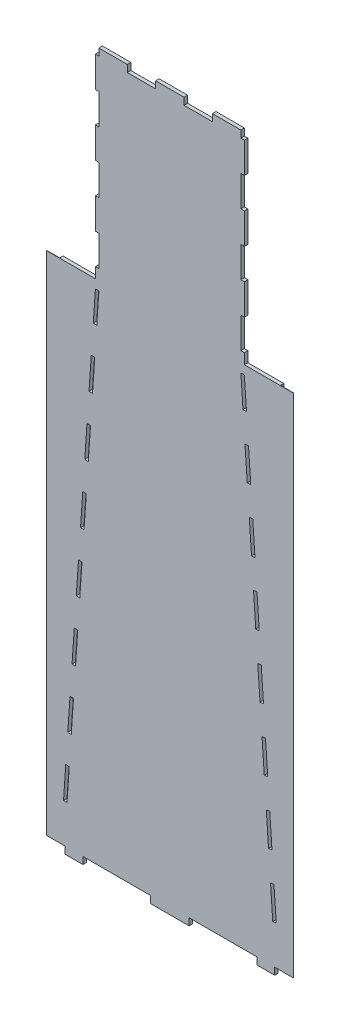
SolidWorks part; units mm, degrees
material "A-Glass Fiber"
ref_plane "Front Plane" through (0, 0, 0) normal (0, 0, 1) x (1, 0, 0)
ref_plane "Top Plane" through (0, 0, 0) normal (0, 1, 0) x (1, 0, 0)
ref_plane "Right Plane" through (0, 0, 0) normal (1, 0, 0) x (0, 0, -1)
sketch "Sketch1" plane through (0, 0, 0) normal (0, 0, 1) x (1, 0, 0)
  line L0 (-215.8818, 2072.64) -> (-215.8818, 1463.04) construction
  line L1 (308.2661, 132.944) -> (301.7555, 226.6808) construction
  line L2 (-303.52, 0) -> (252, 0) construction
  line L3 (-215.8818, 2072.64) -> (215.8818, 2072.64) construction
  line L4 (301.7555, 226.6808) -> (291.6378, 225.9781) construction
  line L5 (-205.7153, 2072.64) -> (-123.444, 2072.64)
  line L6 (-123.444, 2052.32) -> (-123.444, 2072.64)
  line L7 (-123.444, 2052.32) -> (-123.444, 2072.64)
  line L8 (-41.1356, 2072.64) -> (-41.1356, 2052.32)
  line L9 (-41.1356, 2072.64) -> (41.1356, 2072.64)
  line L10 (0, 2072.64) -> (0, 0) construction
  line L11 (291.6378, 225.9781) -> (298.1484, 132.2412) construction
  line L12 (-252, 20.32) -> (252, 20.32)
  line L13 (298.1484, 132.2412) -> (308.2661, 132.944) construction
  line L14 (289.4357, 404.0535) -> (279.318, 403.3508) construction
  line L15 (279.318, 403.3508) -> (285.8305, 309.5874) construction
  line L16 (285.8305, 309.5874) -> (295.9482, 310.2901) construction
  line L17 (-205.7153, 2072.64) -> (-123.444, 2072.64) construction
  line L18 (-205.7153, 2072.64) -> (-205.7153, 1963.42)
  line L19 (-205.7153, 1963.42) -> (-215.8818, 1963.42)
  line L20 (-215.8818, 2052.32) -> (-215.8818, 1963.42)
  line L21 (-205.7153, 1963.42) -> (-215.8818, 1963.42)
  line L23 (-205.7153, 1874.52) -> (-215.8818, 1874.52)
  line L26 (295.9482, 310.2901) -> (289.4357, 404.0535) construction
  line L28 (205.7153, 1696.72) -> (215.8753, 1696.72)
  line L29 (215.8753, 1696.72) -> (215.8753, 1607.82)
  line L30 (205.7153, 1696.72) -> (215.8753, 1696.72)
  line L31 (205.7153, 1607.82) -> (215.8753, 1607.82)
  line L32 (283.6303, 487.6362) -> (277.1159, 581.4262) construction
  line L33 (205.7153, 1607.82) -> (215.8753, 1607.82)
  line L34 (-205.7153, 1518.92) -> (215.8818, 1518.92)
  line L35 (205.7153, 1785.62) -> (215.8818, 1785.62)
  line L36 (-205.7153, 1518.92) -> (215.8818, 1518.92)
  line L37 (-215.8818, 1463.04) -> (-205.7153, 1463.04)
  line L38 (277.1159, 581.4262) -> (266.9983, 580.7234) construction
  line L39 (-215.8818, 1463.04) -> (-205.7153, 1463.04) construction
  line L40 (-205.7153, 1463.04) -> (-205.7153, 2072.64)
  line L41 (266.9983, 580.7234) -> (273.5126, 486.9335) construction
  line L42 (273.5126, 486.9335) -> (283.6303, 487.6362) construction
  line L43 (264.7962, 758.7989) -> (254.6785, 758.0961) construction
  line L44 (215.8818, 1463.04) -> (205.7153, 1463.04) construction
  line L45 (254.6785, 758.0961) -> (261.1947, 664.2796) construction
  line L46 (261.1947, 664.2796) -> (271.3124, 664.9824) construction
  line L47 (271.3124, 664.9824) -> (264.7962, 758.7989) construction
  line L48 (252.4764, 936.1715) -> (242.3588, 935.4688) construction
  line L50 (242.3588, 935.4688) -> (248.8768, 841.6258) construction
  line L52 (248.8768, 841.6258) -> (258.9945, 842.3285) construction
  line L53 (258.9945, 842.3285) -> (252.4764, 936.1715) construction
  line L54 (240.1567, 1113.5442) -> (230.039, 1112.8414) construction
  line L55 (230.039, 1112.8414) -> (236.5589, 1018.9719) construction
  line L56 (236.5589, 1018.9719) -> (246.6766, 1019.6747) construction
  line L57 (246.6766, 1019.6747) -> (240.1567, 1113.5442) construction
  line L58 (227.8369, 1290.9169) -> (217.7192, 1290.2141) construction
  line L59 (217.7192, 1290.2141) -> (224.241, 1196.3181) construction
  line L60 (224.241, 1196.3181) -> (234.3587, 1197.0208) construction
  line L61 (234.3587, 1197.0208) -> (227.8369, 1290.9169) construction
  line L62 (205.7153, 1463.04) -> (211.9231, 1373.6642) construction
  line L63 (211.9231, 1373.6642) -> (222.0407, 1374.3669) construction
  line L64 (222.0407, 1374.3669) -> (215.8818, 1463.04) construction
  line L65 (215.8818, 1463.04) -> (205.7153, 1463.04) construction
  line L66 (-211.9231, 1373.6642) -> (-205.7153, 1463.04) construction
  line L67 (252, 0) -> (303.52, 0) construction
  line L68 (-205.7153, 1463.04) -> (-215.8818, 1463.04) construction
  line L69 (-215.8818, 1463.04) -> (-222.0407, 1374.3669) construction
  line L70 (-252, 20.32) -> (-252, 0)
  line L71 (-222.0407, 1374.3669) -> (-211.9231, 1373.6642) construction
  line L72 (-217.7192, 1290.2141) -> (-227.8369, 1290.9169) construction
  line L73 (-227.8369, 1290.9169) -> (-234.3587, 1197.0208) construction
  line L74 (-234.3587, 1197.0208) -> (-224.241, 1196.3181) construction
  line L75 (-224.241, 1196.3181) -> (-217.7192, 1290.2141) construction
  line L76 (-230.039, 1112.8414) -> (-240.1567, 1113.5442) construction
  line L77 (-240.1567, 1113.5442) -> (-246.6766, 1019.6747) construction
  line L79 (-246.6766, 1019.6747) -> (-236.5589, 1018.9719) construction
  line L80 (-236.5589, 1018.9719) -> (-230.039, 1112.8414) construction
  line L81 (-242.3588, 935.4688) -> (-252.4764, 936.1715) construction
  line L82 (205.7153, 2072.64) -> (123.444, 2072.64) construction
  line L86 (-205.7153, 2052.32) -> (-215.8818, 2052.32)
  line L89 (-252.4764, 936.1715) -> (-258.9945, 842.3285) construction
  line L90 (215.8818, 2072.64) -> (215.8818, 1463.04) construction
  line L91 (-215.8818, 2052.32) -> (-205.7153, 2052.32)
  line L92 (215.8818, 2052.32) -> (205.7153, 2052.32)
  line L94 (205.7153, 2052.32) -> (-215.8818, 2052.32)
  line L98 (-258.9945, 842.3285) -> (-248.8768, 841.6258) construction
  line L99 (-248.8768, 841.6258) -> (-242.3588, 935.4688) construction
  line L101 (-254.6785, 758.0961) -> (-264.7962, 758.7989) construction
  line L102 (-264.7962, 758.7989) -> (-271.3124, 664.9824) construction
  line L104 (-271.3124, 664.9824) -> (-261.1947, 664.2796) construction
  line L105 (-261.1947, 664.2796) -> (-254.6785, 758.0961) construction
  line L106 (-277.1159, 581.4262) -> (-283.6303, 487.6362) construction
  line L107 (-283.6303, 487.6362) -> (-273.5126, 486.9335) construction
  line L108 (252, 20.32) -> (252, 0)
  line L109 (-273.5126, 486.9335) -> (-266.9983, 580.7234) construction
  line L111 (-266.9983, 580.7234) -> (-277.1159, 581.4262) construction
  line L112 (-279.318, 403.3508) -> (-289.4357, 404.0535) construction
  line L113 (-289.4357, 404.0535) -> (-295.9482, 310.2901) construction
  line L114 (-295.9482, 310.2901) -> (-285.8305, 309.5874) construction
  line L116 (-285.8305, 309.5874) -> (-279.318, 403.3508) construction
  line L117 (-301.7555, 226.6808) -> (-308.2661, 132.944) construction
  line L120 (-308.2661, 132.944) -> (-298.1484, 132.2412) construction
  line L121 (-298.1484, 132.2412) -> (-291.6378, 225.9781) construction
  line L124 (-291.6378, 225.9781) -> (-301.7555, 226.6808) construction
  line L125 (308.2661, 132.944) -> (301.7555, 226.6808)
  line L127 (301.7555, 226.6808) -> (291.6378, 225.9781)
  line L128 (205.7153, 1463.04) -> (205.7153, 2072.64)
  line L129 (215.8818, 1463.04) -> (205.7153, 1463.04)
  line L130 (205.7153, 1518.92) -> (-215.8818, 1518.92)
  line L131 (-205.7153, 1518.92) -> (-215.8818, 1518.92)
  line L132 (205.7153, 1518.92) -> (-215.8818, 1518.92)
  line L133 (-205.7153, 1607.82) -> (-215.8753, 1607.82)
  line L134 (291.6378, 225.9781) -> (298.1484, 132.2412)
  line L135 (-205.7153, 1607.82) -> (-215.8753, 1607.82)
  line L136 (-205.7153, 1696.72) -> (-215.8753, 1696.72)
  line L137 (-215.8753, 1696.72) -> (-215.8753, 1607.82)
  line L138 (-205.7153, 1696.72) -> (-215.8753, 1696.72)
  line L143 (-215.8818, 1518.92) -> (-215.8818, 1463.04)
  line L145 (205.7153, 1963.42) -> (215.8818, 1963.42)
  line L146 (215.8818, 2052.32) -> (215.8818, 1963.42)
  line L147 (205.7153, 1963.42) -> (215.8818, 1963.42)
  line L148 (205.7153, 2072.64) -> (205.7153, 1963.42)
  line L149 (41.1356, 2072.64) -> (41.1356, 2052.32)
  line L150 (123.444, 2052.32) -> (123.444, 2072.64)
  line L151 (123.444, 2052.32) -> (123.444, 2072.64)
  line L152 (205.7153, 2072.64) -> (123.444, 2072.64)
  line L153 (298.1484, 132.2412) -> (308.2661, 132.944)
  line L154 (205.7153, 1518.92) -> (215.8818, 1518.92)
  line L155 (215.8818, 1518.92) -> (215.8818, 1463.04)
  line L156 (-205.7153, 1785.62) -> (-215.8818, 1785.62)
  line L165 (-215.8818, 1874.52) -> (-215.8818, 1785.62)
  line L166 (215.8818, 1874.52) -> (215.8818, 1785.62)
  line L167 (205.7153, 1874.52) -> (215.8818, 1874.52)
  line L168 (215.8818, 1488.44) -> (358.1218, 1488.44)
  line L169 (-55.8292, 20.32) -> (55.8292, 20.32)
  line L170 (-55.8292, 20.32) -> (-55.8292, 0)
  line L171 (-55.8292, 0) -> (55.8292, 0)
  line L172 (55.8292, 20.32) -> (55.8292, 0)
  line L173 (358.1218, 1488.44) -> (358.1218, 20.32)
  line L175 (-215.8818, 1488.44) -> (-358.1218, 1488.44)
  line L176 (-358.1218, 1488.44) -> (-358.1218, 20.32)
  line L178 (289.4357, 404.0535) -> (279.318, 403.3508)
  line L179 (279.318, 403.3508) -> (285.8305, 309.5874)
  line L180 (-371.5407, 0) -> (-280.9748, 0) construction
  line L181 (-358.1218, 20.32) -> (-303.52, 20.32)
  line L184 (-303.52, 20.32) -> (-303.52, 0)
  line L185 (280.9748, 0) -> (371.5407, 0) construction
  line L186 (-303.52, 0) -> (-252, 0)
  line L187 (-303.52, 0) -> (-303.52, 20.32)
  line L189 (-252, 0) -> (-252, 20.32)
  line L190 (358.1218, 20.32) -> (303.52, 20.32)
  line L193 (303.52, 20.32) -> (303.52, 0)
  line L194 (285.8305, 309.5874) -> (295.9482, 310.2901)
  line L195 (303.52, 0) -> (252, 0)
  line L196 (303.52, 0) -> (303.52, 20.32)
  line L198 (252, 0) -> (252, 20.32)
  line L199 (295.9482, 310.2901) -> (289.4357, 404.0535)
  line L200 (283.6303, 487.6362) -> (277.1159, 581.4262)
  line L201 (277.1159, 581.4262) -> (266.9983, 580.7234)
  line L202 (266.9983, 580.7234) -> (273.5126, 486.9335)
  line L203 (273.5126, 486.9335) -> (283.6303, 487.6362)
  line L204 (264.7962, 758.7989) -> (254.6785, 758.0961)
  line L205 (254.6785, 758.0961) -> (261.1947, 664.2796)
  line L206 (261.1947, 664.2796) -> (271.3124, 664.9824)
  line L207 (271.3124, 664.9824) -> (264.7962, 758.7989)
  line L208 (252.4764, 936.1715) -> (242.3588, 935.4688)
  line L209 (242.3588, 935.4688) -> (248.8768, 841.6258)
  line L210 (248.8768, 841.6258) -> (258.9945, 842.3285)
  line L211 (258.9945, 842.3285) -> (252.4764, 936.1715)
  line L212 (240.1567, 1113.5442) -> (230.039, 1112.8414)
  line L213 (230.039, 1112.8414) -> (236.5589, 1018.9719)
  line L214 (236.5589, 1018.9719) -> (246.6766, 1019.6747)
  line L215 (246.6766, 1019.6747) -> (240.1567, 1113.5442)
  line L216 (227.8369, 1290.9169) -> (217.7192, 1290.2141)
  line L217 (217.7192, 1290.2141) -> (224.241, 1196.3181)
  line L218 (224.241, 1196.3181) -> (234.3587, 1197.0208)
  line L219 (234.3587, 1197.0208) -> (227.8369, 1290.9169)
  line L220 (205.7153, 1463.04) -> (211.9231, 1373.6642)
  line L221 (211.9231, 1373.6642) -> (222.0407, 1374.3669)
  line L222 (222.0407, 1374.3669) -> (215.8818, 1463.04)
  line L223 (215.8818, 1463.04) -> (205.7153, 1463.04)
  line L224 (-211.9231, 1373.6642) -> (-205.7153, 1463.04)
  line L225 (-205.7153, 1463.04) -> (-215.8818, 1463.04)
  line L226 (-215.8818, 1463.04) -> (-222.0407, 1374.3669)
  line L227 (-222.0407, 1374.3669) -> (-211.9231, 1373.6642)
  line L228 (-217.7192, 1290.2141) -> (-227.8369, 1290.9169)
  line L229 (-227.8369, 1290.9169) -> (-234.3587, 1197.0208)
  line L230 (-234.3587, 1197.0208) -> (-224.241, 1196.3181)
  line L231 (-224.241, 1196.3181) -> (-217.7192, 1290.2141)
  line L232 (-230.039, 1112.8414) -> (-240.1567, 1113.5442)
  line L233 (-240.1567, 1113.5442) -> (-246.6766, 1019.6747)
  line L234 (-246.6766, 1019.6747) -> (-236.5589, 1018.9719)
  line L235 (-236.5589, 1018.9719) -> (-230.039, 1112.8414)
  line L236 (-242.3588, 935.4688) -> (-252.4764, 936.1715)
  line L237 (-252.4764, 936.1715) -> (-258.9945, 842.3285)
  line L238 (-258.9945, 842.3285) -> (-248.8768, 841.6258)
  line L239 (-248.8768, 841.6258) -> (-242.3588, 935.4688)
  line L240 (-254.6785, 758.0961) -> (-264.7962, 758.7989)
  line L241 (-264.7962, 758.7989) -> (-271.3124, 664.9824)
  line L242 (-271.3124, 664.9824) -> (-261.1947, 664.2796)
  line L243 (-261.1947, 664.2796) -> (-254.6785, 758.0961)
  line L244 (-277.1159, 581.4262) -> (-283.6303, 487.6362)
  line L245 (-283.6303, 487.6362) -> (-273.5126, 486.9335)
  line L246 (-273.5126, 486.9335) -> (-266.9983, 580.7234)
  line L247 (-266.9983, 580.7234) -> (-277.1159, 581.4262)
  line L248 (-279.318, 403.3508) -> (-289.4357, 404.0535)
  line L249 (-289.4357, 404.0535) -> (-295.9482, 310.2901)
  line L250 (-295.9482, 310.2901) -> (-285.8305, 309.5874)
  line L251 (-285.8305, 309.5874) -> (-279.318, 403.3508)
  line L252 (-301.7555, 226.6808) -> (-308.2661, 132.944)
  line L253 (-308.2661, 132.944) -> (-298.1484, 132.2412)
  line L254 (-298.1484, 132.2412) -> (-291.6378, 225.9781)
  line L255 (-291.6378, 225.9781) -> (-301.7555, 226.6808)
  line L258 (358.1218, 1488.44) -> (358.1218, 20.32)
  point P11 (-252, 10.16)
  point P130 (-210.7985, 1463.04)
  point P141 (0, 20.32)
  dimension "D3" = 609.6
  dimension "D4" = 2072.64
  dimension "D5" = 20.32
  dimension "D6" = 88.9
  dimension "D7" = 20.32
  dimension "D9" = 41.1356
  dimension "D10" = 10.1665
  dimension "D11" = 205.7153
  dimension "D12" = 10.16
  dimension "D13" = 10.16
  dimension "D14" = 88.9
  dimension "D15" = 88.9
  dimension "D16" = 88.9
  dimension "D18" = 88.9
  dimension "D20" = 88.9
  dimension "D21" = 20.32
  dimension "D22" = 142.24
  dimension "D23" = 142.24
  dimension "D24" = 25.4
  dimension "D25" = 25.4
  dimension "D26" = 252
  dimension "D27" = 51.52
extrude "Boss-Extrude1" add sketch "Sketch1" along normal blind 10.16
sketch "Sketch2" plane through (0, 0, 0) normal (0, 1, 0) x (1, 0, 0)
  line L1 (358.1218, 0) -> (320.0218, 0)
  line L2 (358.1218, 0) -> (358.1218, -9.5)
  line L3 (358.1218, -9.5) -> (320.0218, -9.5)
  line L4 (320.0218, 0) -> (320.0218, -9.5)
  line L5 (0, 0) -> (0, -34.3067) construction
  line L6 (0, -5.588) -> (0, 5.588) construction
  line L7 (-320.0218, 0) -> (-320.0218, -9.5)
  line L8 (-358.1218, -9.5) -> (-320.0218, -9.5)
  line L9 (-358.1218, 0) -> (-358.1218, -9.5)
  line L10 (-358.1218, 0) -> (-320.0218, 0)
  dimension "D1" = 38.1
  dimension "D2" = 9.5
extrude "Cut-Extrude1" cut sketch "Sketch2" along normal blind 2540
